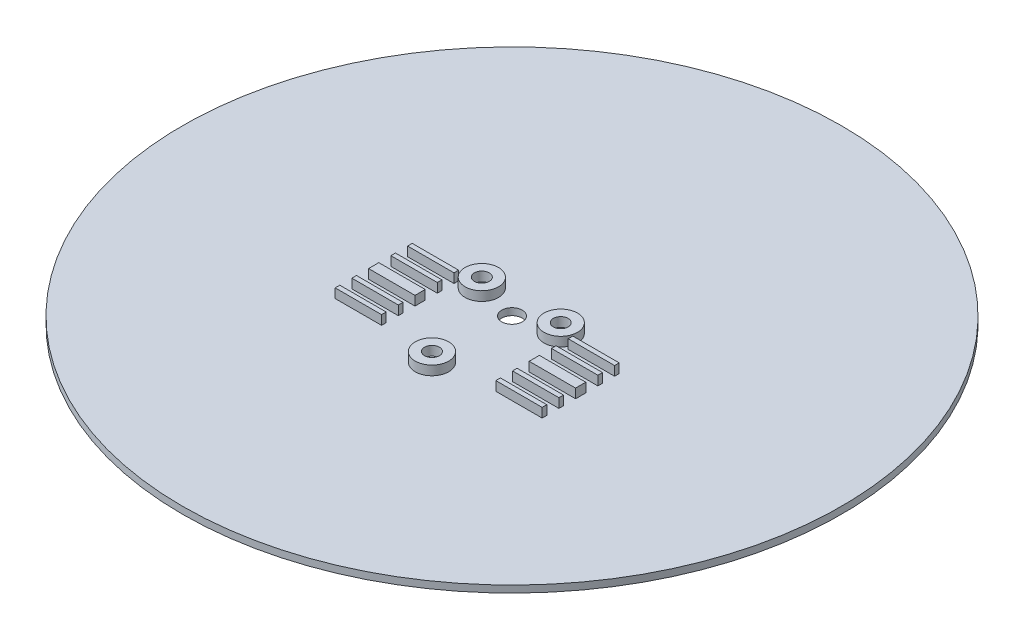
SolidWorks part; units mm, degrees
ref_plane "Front Plane" through (0, 0, 0) normal (0, 0, 1) x (1, 0, 0)
ref_plane "Top Plane" through (0, 0, 0) normal (0, 1, 0) x (1, 0, 0)
ref_plane "Right Plane" through (0, 0, 0) normal (1, 0, 0) x (0, 0, -1)
sketch "Sketch1" plane through (0, 0, 0) normal (0, 1, 0) x (1, 0, 0)
  circle A0 centre (0, 0) radius 71
  circle A1 centre (0, 0) radius 1.5
extrude "Boss-Extrude1" add sketch "Sketch1" along normal blind 1.5 contours A0
sketch "Sketch2" plane through (0, 1.5, 0) normal (0, 1, 0) x (1, 0, 0)
  circle A0 centre (0, 0) radius 2.2
extrude "Cut-Extrude1" cut sketch "Sketch2" against normal blind 14.5
sketch "Sketch3" plane through (0, 1.5, 0) normal (0, 1, 0) x (1, 0, 0)
  circle A0 centre (8.5, 2) radius 1.6
  circle A1 centre (-8.5, 2) radius 1.6
  circle A2 centre (0, -17.24) radius 1.6
  circle A3 centre (-8.5, 2) radius 3.6
  circle A5 centre (8.5, 2) radius 3.6
  circle A6 centre (0, -17.24) radius 3.6
  dimension "D1" = 8.5
  dimension "D7" = 2
  dimension "D8" = 2
  dimension "D9" = 2
  dimension "D2" = 0
  dimension "D3" = 19.24
  dimension "D4" = 2
  dimension "D5" = 19.24
  dimension "D6" = 8.5
extrude "Boss-Extrude2" add sketch "Sketch3" along normal blind 2
sketch "Sketch4" plane through (0, 1.5, 0) normal (0, 1, 0) x (1, 0, 0)
  line L1 (-12.3, -6.4) -> (-22.3, -6.4)
  line L2 (-12.3, -6.4) -> (-12.3, -8.6)
  line L3 (-12.3, -8.6) -> (-22.3, -8.6)
  line L4 (-22.3, -6.4) -> (-22.3, -8.6)
  line L12 (0, 0) -> (0, -10.6604)
  line L13 (-16.6564, -11.2) -> (-22.3, -11.2)
  line L14 (-22.3, -11.2) -> (-22.3, -12.195)
  line L15 (-22.3, -12.195) -> (-17.0279, -12.195)
  line L41 (-16.6564, -11.2) -> (-12.3, -11.2)
  line L42 (-12.3, -11.2) -> (-12.3, -12.195)
  line L43 (-12.3, -12.195) -> (-17.0279, -12.195)
  line L44 (-16.6564, -11.2) -> (-12.3, -11.2)
  line L45 (-12.3, -12.195) -> (-17.0279, -12.195)
  line L46 (-12.3, -11.2) -> (-12.3, -12.195)
  line L47 (-17.0279, -12.195) -> (-22.3, -12.195)
  line L48 (-22.3, -11.2) -> (-12.3, -11.2)
  line L49 (-12.3, -12.195) -> (-22.3, -12.195)
  line L50 (-22.3, -3.8) -> (-12.3, -3.8)
  line L51 (-12.3, -3.8) -> (-12.3, -2.8045)
  line L52 (-12.3, -2.8045) -> (-22.3, -2.8045)
  line L53 (-22.3, -2.8045) -> (-22.3, -3.8)
  line L54 (-15.5, -1.5) -> (-19.4897, -1.5)
  line L55 (-12.3, -0.1955) -> (-22.3, -0.1955)
  line L56 (-12.3, 0.8) -> (-12.3, -0.1955)
  line L57 (-22.3, 0.8) -> (-12.3, 0.8)
  line L58 (-22.3, -0.1955) -> (-22.3, 0.8)
  line L59 (-15.5, -13.5) -> (-18.3657, -13.5)
  line L60 (-22.3, -15.8) -> (-22.3, -14.805)
  line L61 (-16.6564, -15.8) -> (-22.3, -15.8)
  line L62 (-16.6564, -15.8) -> (-12.3, -15.8)
  line L63 (-12.3, -15.8) -> (-12.3, -14.805)
  line L64 (-12.3, -14.805) -> (-17.0279, -14.805)
  line L65 (-22.3, -14.805) -> (-17.0279, -14.805)
  line L66 (16.6564, -15.8) -> (22.3, -15.8)
  line L67 (16.6564, -15.8) -> (12.3, -15.8)
  line L68 (12.3, -15.8) -> (12.3, -14.805)
  line L69 (12.3, -14.805) -> (17.0279, -14.805)
  line L70 (22.3, -14.805) -> (17.0279, -14.805)
  line L71 (22.3, -15.8) -> (22.3, -14.805)
  line L72 (12.3, -12.195) -> (17.0279, -12.195)
  line L73 (12.3, -11.2) -> (12.3, -12.195)
  line L74 (16.6564, -11.2) -> (12.3, -11.2)
  line L75 (16.6564, -11.2) -> (22.3, -11.2)
  line L76 (22.3, -11.2) -> (22.3, -12.195)
  line L77 (22.3, -12.195) -> (17.0279, -12.195)
  line L78 (12.3, -8.6) -> (22.3, -8.6)
  line L79 (22.3, -6.4) -> (22.3, -8.6)
  line L80 (12.3, -6.4) -> (22.3, -6.4)
  line L81 (12.3, -6.4) -> (12.3, -8.6)
  line L82 (12.3, -2.8045) -> (22.3, -2.8045)
  line L83 (12.3, -3.8) -> (12.3, -2.8045)
  line L84 (22.3, -3.8) -> (12.3, -3.8)
  line L85 (22.3, -2.8045) -> (22.3, -3.8)
  line L86 (12.3, 0.8) -> (12.3, -0.1955)
  line L87 (22.3, 0.8) -> (12.3, 0.8)
  line L88 (22.3, -0.1955) -> (22.3, 0.8)
  line L89 (12.3, -0.1955) -> (22.3, -0.1955)
  circle A0 centre (-12.3, -10.8) radius 1
  circle A1 centre (-12.3, -4.2) radius 1
  circle A2 centre (-15.5, -13.5) radius 1
  circle A3 centre (-15.5, -1.5) radius 1
  circle A4 centre (-8.5, 2) radius 1.6 construction
  circle A5 centre (15.5, -15.5) radius 1
  circle A6 centre (12.3, -12.8) radius 1
  circle A7 centre (15.5, -1.5) radius 1
  circle A8 centre (12.3, -4.2) radius 1
  dimension "D1" = 6.6
  dimension "D5" = 6.2
  dimension "D2" = 12
  dimension "D3" = 7
  dimension "D4" = 3.2
  dimension "D6" = 2.7
  dimension "D7" = 2.2
  dimension "D8" = 10
  dimension "D9" = 2.2
  dimension "D10" = 0
  dimension "D11" = 2.6
  dimension "D12" = 2.6
extrude "Boss-Extrude3" add sketch "Sketch4" along normal blind 2 contours L58 L55 L56 L57 | L1 L4 L3 L2 | A0 L41 L13 L14 L15 L43 L46 | L65 L60 L61 L62 L63 L64 | L69 A5 L67 L66 L71 L70 | L67 A5 L69 L68 | A5 L67 L69 | L73 A6 L72 L77 L76 L75 L74 | L80 L81 L78 L79 | L86 L89 L88 L87 | A6 L73 L72 | L48 A0 L42 | L52 L53 L50 L51 | L82 L85 L84 L83
